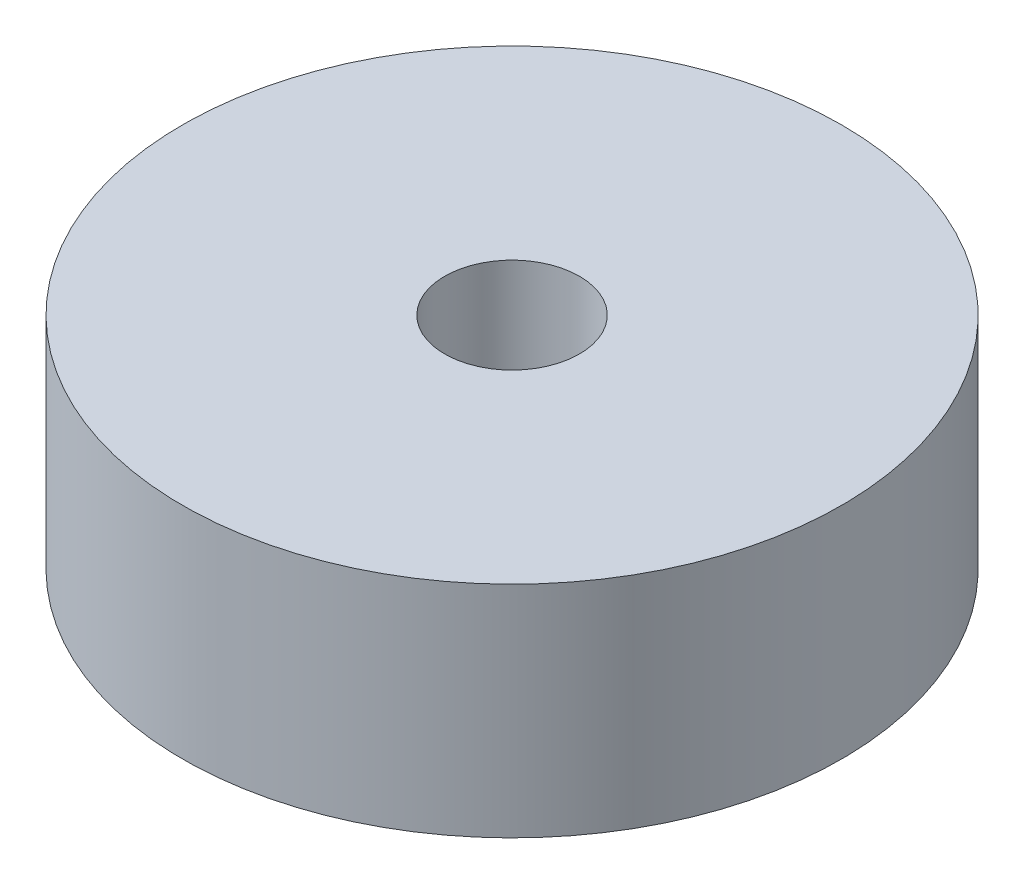
SolidWorks part; units mm, degrees
ref_plane "Front Plane" through (0, 0, 0) normal (0, 0, 1) x (1, 0, 0)
ref_plane "Top Plane" through (0, 0, 0) normal (0, 1, 0) x (1, 0, 0)
ref_plane "Right Plane" through (0, 0, 0) normal (1, 0, 0) x (0, 0, -1)
sketch "Sketch2" plane through (0, 0, 0) normal (0, 1, 0) x (1, 0, 0)
  circle A0 centre (0, 0) radius 28.575
  circle A1 centre (0, 0) radius 5.842
  dimension "D1" = 57.15
  dimension "D2" = 11.684
extrude "Boss-Extrude1" add sketch "Sketch2" along normal blind 19.05
